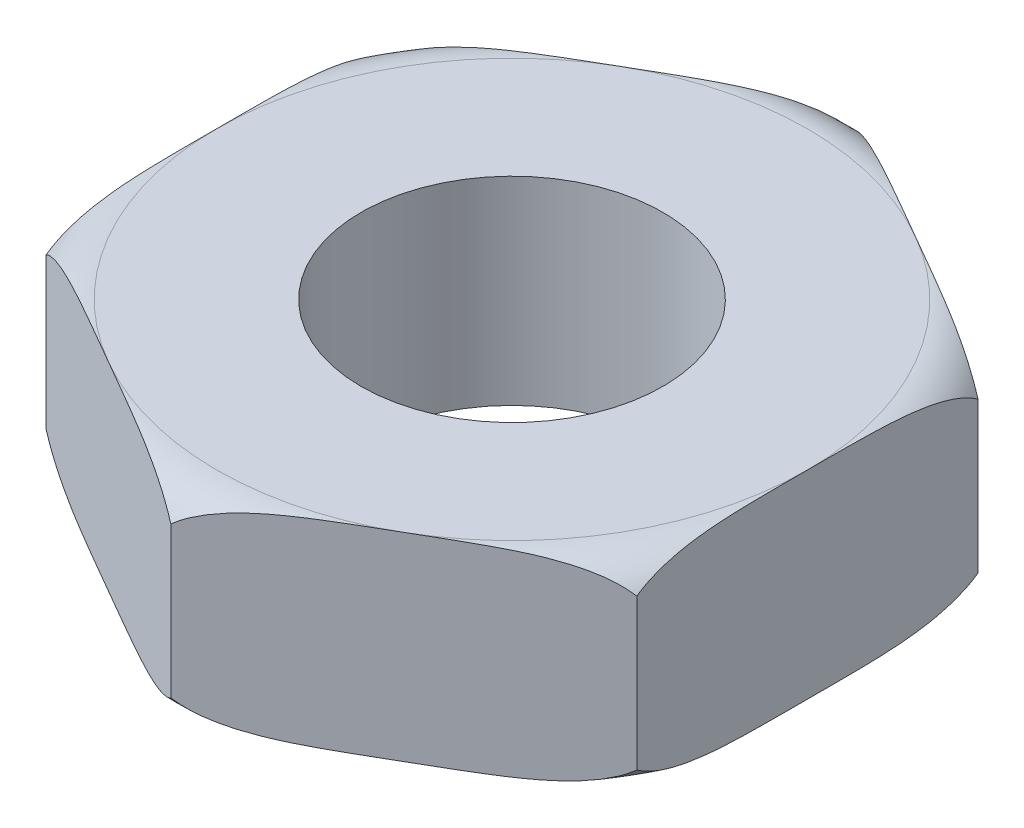
SolidWorks part; units mm, degrees
material "AISI 316 Stainless Steel Sheet (SS)"
ref_plane "Front" through (0, 0, 0) normal (0, 0, 1) x (1, 0, 0)
ref_plane "Top" through (0, 0, 0) normal (0, 1, 0) x (1, 0, 0)
ref_plane "Right" through (0, 0, 0) normal (1, 0, 0) x (0, 0, -1)
sketch "Sketch2" plane through (0, 0, 0) normal (0, 1, 0) x (1, 0, 0)
  line L1 (4.7244, 2.7276) -> (0, 5.4553)
  line L2 (0, 5.4553) -> (-4.7244, 2.7276)
  line L3 (-4.7244, 2.7276) -> (-4.7244, -2.7276)
  line L4 (-4.7244, -2.7276) -> (0, -5.4553)
  line L5 (0, -5.4553) -> (4.7244, -2.7276)
  line L6 (4.7244, -2.7276) -> (4.7244, 2.7276)
  circle A0 centre (0, 0) radius 4.7244 construction
  circle A1 centre (0, 0) radius 2.413
  dimension "D2" = 4.826
  dimension "D1" = 9.4488
extrude "Boss-Extrude2" add sketch "Sketch2" against normal blind 3.175 separate body
sketch "Sketch4" plane through (0, 0, 0) normal (1, 0, 0) x (0, 0, -1)
  line L1 (4.7244, 0) -> (0, 0)
  line L3 (5.4553, -0.3829) -> (5.4553, 0.4794)
  line L4 (0, 0) -> (0, 0.4794)
  line L5 (0, 0.4794) -> (5.4553, 0.4794)
  line L6 (0, -0.2576) -> (0, -1.1963) construction
  line L7 (2.7276, 0) -> (-2.7276, 0) construction
  line L8 (-2.312, -1.5875) -> (-1.9153, -1.5875) construction
  line L9 (-5.4553, -3.175) -> (-5.4553, 0) construction
  line L10 (0, -3.6544) -> (5.4553, -3.6544)
  line L11 (0, -3.175) -> (0, -3.6544)
  line L12 (5.4553, -2.7921) -> (5.4553, -3.6544)
  line L13 (4.7244, -3.175) -> (0, -3.175)
  line L16 (5.4553, -3.175) -> (5.4553, 0) construction
  arc A0 (5.4553, -0.3829) -> (4.7244, 0) centre (4.7244, -0.889) ccw
  arc A1 (5.4553, -2.7921) -> (4.7244, -3.175) centre (4.7244, -2.286) cw
  point P2 (0, 0)
  point P3 (0, 0)
  point P16 (-5.4553, -1.5875)
  point P23 (0, 0)
  point P24 (0, 0)
  point P25 (0, 0)
  point P26 (5.3135, 1.2886)
  point P27 (0, 0)
  point P28 (0, 0)
  point P29 (5.2942, -2.0075)
  point P30 (0, 0)
  point P31 (0, 0)
  point P32 (0, 0)
  point P33 (0, 0)
  point P34 (0, 0)
  point P36 (4.7873, -0.635)
  point P39 (4.8328, -0.635)
  point P40 (4.6319, -1.016)
  point P41 (4.4911, -1.016)
  point P42 (4.4229, -1.27)
  dimension "D1" = 0.889
  dimension "D2" = 4.7244
revolve "Cut-Revolve1" cut sketch "Sketch4" angle 360 about L6
